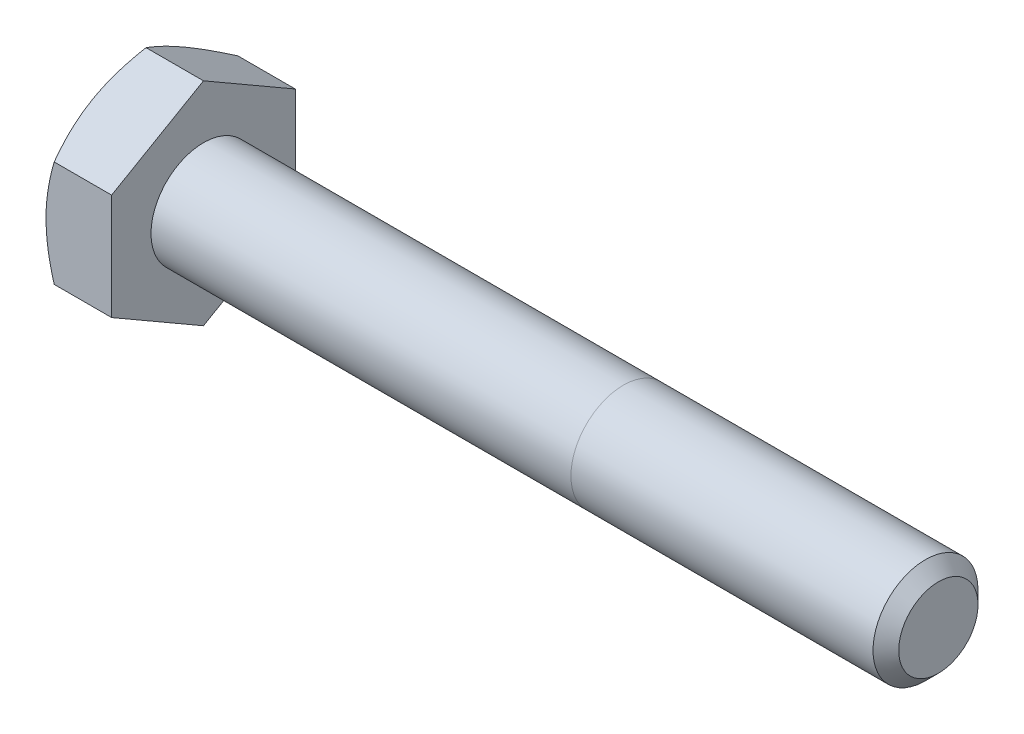
SolidWorks part; units mm, degrees
material "Alloy Steel"
ref_plane "Front Plane" through (0, 0, 0) normal (0, 0, 1) x (1, 0, 0)
ref_plane "Top Plane" through (0, 0, 0) normal (0, 1, 0) x (1, 0, 0)
ref_plane "Right Plane" through (0, 0, 0) normal (1, 0, 0) x (0, 0, -1)
sketch "Sketch1" plane through (0, 0, 0) normal (0, 0, 1) x (1, 0, 0)
  line L0 (-24.2094, 0) -> (24.2094, 0) construction
  line L1 (24.2094, 3.175) -> (24.2094, -3.175) construction
  line L2 (-20.2406, 5.5562) -> (-20.2406, -5.5562) construction
  line L3 (-24.2094, 5.5562) -> (-24.2094, -5.5562) construction
  point P9 (-20.2406, 0)
  point P10 (19.7644, -3.175)
  dimension "D1" = 4.445
  dimension "Screw Dia" = 6.35
  dimension "Hex" = 11.1125
  dimension "Head Ht" = 3.9688
  dimension "Screw Lenght" = 44.45
ref_plane "Plane2" through (24.2094, 0, 0) normal (1, 0, 0) x (0, 0, -1)
sketch "Sketch5" plane through (24.2094, 0, 0) normal (1, 0, 0) x (0, 0, -1)
  circle A0 centre (0, 0) radius 3.175
extrude "Boss-Extrude3" add sketch "Sketch5" against normal up to vertex (44.45 mm away) up to point (-20.2406, 0, 0)
sketch "Sketch9" plane through (24.2094, 0, 0) normal (1, 0, 0) x (0, 0, -1)
  circle A1 centre (0, 0) radius 3.175
  circle A2 centre (0, 0) radius 3.175
  dimension "D1" = 0
curve "Helix/Spiral1" pitch 1.27 height 45.72 turns 36 parameters "Pitch"=1.27
chamfer "Chamfer1" distance 0.7772 angle 45 1 edges at (24.2094, 0, -3.175)
sketch "Sketch10" plane through (0, 0, 0) normal (0, 0, 1) x (1, 0, 0)
  line L0 (24.2094, 3.175) -> (24.6856, 2.3501)
  line L1 (24.6856, 2.3501) -> (24.8444, 2.3501)
  line L2 (24.8444, 2.3501) -> (25.3206, 3.175)
  line L3 (24.2094, 3.175) -> (25.3206, 3.175)
  line L4 (24.765, 3.175) -> (24.765, 2.3501) construction
  line L5 (24.4475, 2.7626) -> (25.0825, 2.7626) construction
  dimension "D1" = 60
  dimension "D2" = 0.1588
  dimension "D3" = 0.635
sketch "Sketch6" plane through (-20.2406, 0, 0) normal (-1, 0, 0) x (0, 0, 1)
  line L0 (0, 5.5562) -> (0, -5.5562) construction
  line L1 (5.5563, 3.2079) -> (0, 6.4158)
  line L2 (0, 6.4158) -> (-5.5562, 3.2079)
  line L3 (-5.5562, 3.2079) -> (-5.5562, -3.2079)
  line L4 (-5.5562, -3.2079) -> (0, -6.4158)
  line L5 (0, -6.4158) -> (5.5563, -3.2079)
  line L6 (5.5563, -3.2079) -> (5.5563, 3.2079)
  circle A0 centre (0, 0) radius 5.5563 construction
extrude "Boss-Extrude4" add sketch "Sketch6" along normal up to vertex (3.9688 mm away) up to point (-24.2094, -5.5562, 0)
sketch "Sketch7" plane through (-24.2094, 0, 0) normal (-1, 0, 0) x (0, 0, 1)
  circle A0 centre (0, 0) radius 5.5563 construction
  circle A1 centre (0, 0) radius 5.5563
sketch "Sketch8" plane through (-24.2094, 0, 0) normal (-1, 0, 0) x (0, 0, 1)
  circle A0 centre (0, 0) radius 5.5563 construction
  circle A1 centre (0, 0) radius 5.5563
extrude "Cut-Extrude3" cut sketch "Sketch8" against normal through all draft 60 flip side to cut
sketch "Sketch12" plane through (-24.2094, 0, 0) normal (-1, 0, 0) x (0, 0, 1)
  line L0 (0, 4.2783) -> (0, 2.3892) construction
  line L1 (0.1667, 4.2783) -> (0.1667, 2.3892)
  line L2 (-0.1667, 4.2783) -> (-0.1667, 2.3892)
  line L3 (0, 3.175) -> (0, -3.175) construction
  arc A0 (0.1667, 4.2783) -> (-0.1667, 4.2783) centre (0, 4.2783) ccw
  arc A1 (-0.1667, 2.3892) -> (0.1667, 2.3892) centre (0, 2.3892) ccw
  circle A3 centre (0, 0) radius 2.2225 construction
  circle A4 centre (0, 0) radius 4.445 construction
  point P2 (0, 3.3337)
  dimension "D1" = 4.445
  dimension "D3" = 8.89
  dimension "D2" = 0.3334
extrude "Cut-Extrude4" cut sketch "Sketch12" against normal blind 0.254
pattern_circular "CirPattern1" count 3 over 360 about axis through (0, 0, 0) along (1, 0, 0) of "Cut-Extrude4"
sketch "Sketch13" plane through (0, 0, 0) normal (0, 1, 0) x (1, 0, 0)
  line L0 (5.1594, 3.175) -> (5.1594, -3.175)
  line L1 (23.4321, 3.175) -> (-20.2406, 3.175) construction
  line L2 (-20.2406, -3.175) -> (23.4321, -3.175) construction
  line L3 (24.2094, -2.3978) -> (24.2094, 2.3978) construction
  dimension "D1" = 19.05
split line "Split Line2"
equation "\"D2@Sketch10\" = \"Pitch@Helix/Spiral1\"*.125"
equation "\"D3@Sketch10\" = \"Pitch@Helix/Spiral1\"*.5"
equation "\"D1@Chamfer1\" = \"Pitch@Helix/Spiral1\"*.612"
equation "\"D1@Sketch12\" = \"Hex@Sketch1\"*.4"
equation "\"D3@Sketch12\" = \"Hex@Sketch1\"*.8"
equation "\"D2@Sketch12\" = \"Hex@Sketch1\"*.03"
equation "\"D1@Sketch1\" = \"Pitch@Helix/Spiral1\"*3.5"
equation "\"D3@Helix/Spiral1\" = \"Screw Lenght@Sketch1\"+\"Pitch@Helix/Spiral1\""
